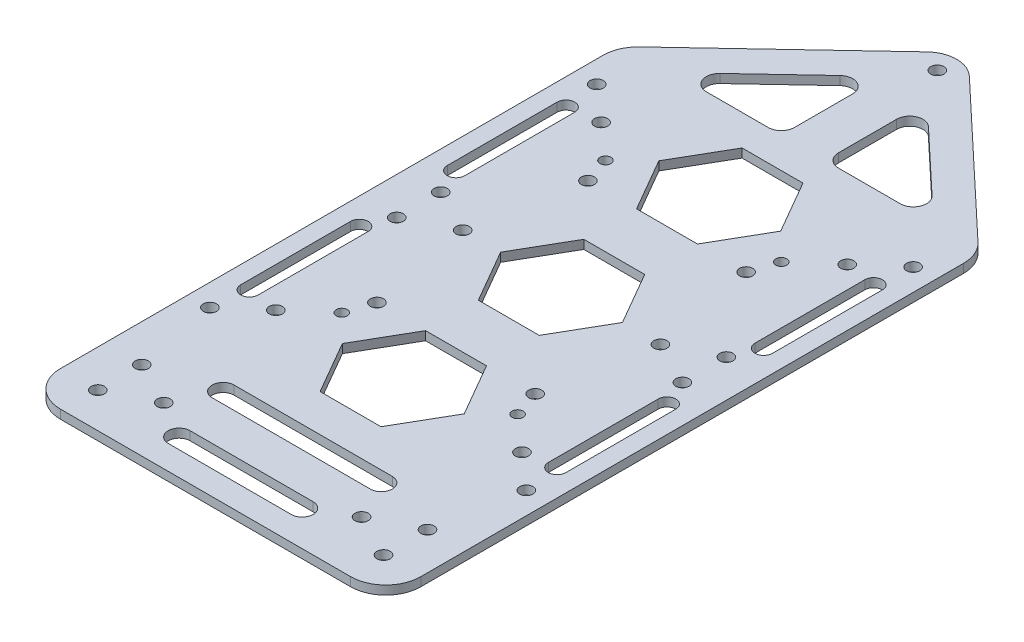
SolidWorks part; units mm, degrees
ref_plane "前视基准面" through (0, 0, 0) normal (0, 0, 1) x (1, 0, 0)
ref_plane "上视基准面" through (0, 0, 0) normal (0, 1, 0) x (1, 0, 0)
ref_plane "右视基准面" through (0, 0, 0) normal (1, 0, 0) x (0, 0, -1)
sketch "草图1" plane through (0, 0, 0) normal (0, 1, 0) x (1, 0, 0)
  line L0 (-33, -81) -> (33, -81)
  line L2 (-41, -73) -> (-41, 50.4441)
  line L4 (41, -73) -> (41, 50.4441)
  line L5 (-41, -92.5) -> (41, 92.5) construction
  line L6 (-41, 92.5) -> (41, -92.5) construction
  line L11 (-20, -30) -> (20, -30) construction
  line L12 (-20, -30) -> (-20, 30) construction
  line L13 (-20, 30) -> (20, 30) construction
  line L14 (20, -30) -> (20, 30) construction
  line L15 (-20, -30) -> (20, 30) construction
  line L16 (-20, 30) -> (20, -30) construction
  line L17 (-36, -44) -> (36, -44) construction
  line L18 (-36, -44) -> (-36, 44) construction
  line L19 (-36, 44) -> (36, 44) construction
  line L20 (36, -44) -> (36, 44) construction
  line L21 (-36, -44) -> (36, 44) construction
  line L22 (-36, 44) -> (36, -44) construction
  line L27 (-32.5, 5) -> (-32.5, -63) construction
  line L28 (-32.5, -5) -> (32.5, -5) construction
  line L29 (-32.5, -5) -> (-32.5, 5) construction
  line L30 (-32.5, 5) -> (32.5, 5) construction
  line L31 (32.5, -5) -> (32.5, 5) construction
  line L32 (-32.5, -5) -> (32.5, 5) construction
  line L33 (-32.5, 5) -> (32.5, -5) construction
  line L38 (-4.7983, 87.9825) -> (-38.4838, 56.2689)
  line L39 (4.7983, 87.9825) -> (38.4838, 56.2689)
  line L41 (-18, -24) -> (18, -24) construction
  line L42 (-18, -24) -> (-18, 24) construction
  line L43 (-18, 24) -> (18, 24) construction
  line L44 (18, -24) -> (18, 24) construction
  line L45 (-18, -24) -> (18, 24) construction
  line L46 (-18, 24) -> (18, -24) construction
  line L47 (-35, 11) -> (-35, 36) construction
  line L48 (-37, 11) -> (-37, 36)
  line L49 (-33, 11) -> (-33, 36)
  line L50 (35, 11) -> (35, 36) construction
  line L51 (33, 11) -> (33, 36)
  line L52 (37, 11) -> (37, 36)
  line L53 (35, -36) -> (35, -11) construction
  line L54 (33, -36) -> (33, -11)
  line L55 (37, -36) -> (37, -11)
  line L56 (-35, -36) -> (-35, -11) construction
  line L57 (-37, -36) -> (-37, -11)
  line L58 (-33, -36) -> (-33, -11)
  line L60 (-28, -37) -> (28, -37) construction
  line L61 (-28, -37) -> (-28, 37) construction
  line L62 (-28, 37) -> (28, 37) construction
  line L63 (28, -37) -> (28, 37) construction
  line L64 (-28, -37) -> (28, 37) construction
  line L65 (-28, 37) -> (28, -37) construction
  circle A0 centre (-20, 30) radius 1.25
  circle A1 centre (20, 30) radius 1.25
  circle A2 centre (20, -30) radius 1.25
  circle A3 centre (-20, -30) radius 1.25
  circle A4 centre (0, 85.5) radius 1.5
  circle A7 centre (-36, 44) radius 1.5
  circle A8 centre (36, 44) radius 1.5
  circle A9 centre (36, -44) radius 1.5
  circle A10 centre (-36, -44) radius 1.5
  circle A11 centre (-32.5, 5) radius 1.5
  circle A12 centre (-32.5, -5) radius 1.5
  circle A13 centre (32.5, 5) radius 1.5
  circle A14 centre (32.5, -5) radius 1.5
  circle A15 centre (22.5, 0) radius 1.5
  circle A16 centre (-22.5, 0) radius 1.5
  circle A17 centre (-32.5, -63) radius 1.5
  circle A18 centre (-32.5, -73) radius 1.5
  circle A19 centre (-22.5, -68) radius 1.5
  circle A20 centre (32.5, -63) radius 1.5
  circle A21 centre (22.5, -68) radius 1.5
  circle A22 centre (32.5, -73) radius 1.5
  arc A26 (38.4838, 56.2689) -> (41, 50.4441) centre (33, 50.4441) cw
  arc A27 (-4.7983, 87.9825) -> (4.7983, 87.9825) centre (0, 82.8859) cw
  arc A28 (-38.4838, 56.2689) -> (-41, 50.4441) centre (-33, 50.4441) ccw
  arc A29 (41, -73) -> (33, -81) centre (33, -73) cw
  arc A30 (-41, -73) -> (-33, -81) centre (-33, -73) ccw
  circle A31 centre (-18, 24) radius 1.5
  circle A32 centre (18, 24) radius 1.5
  circle A33 centre (18, -24) radius 1.5
  circle A34 centre (-18, -24) radius 1.5
  arc A35 (-37, 11) -> (-33, 11) centre (-35, 11) ccw
  arc A36 (-33, 36) -> (-37, 36) centre (-35, 36) ccw
  arc A37 (33, 11) -> (37, 11) centre (35, 11) ccw
  arc A38 (37, 36) -> (33, 36) centre (35, 36) ccw
  arc A39 (33, -36) -> (37, -36) centre (35, -36) ccw
  arc A40 (37, -11) -> (33, -11) centre (35, -11) ccw
  arc A41 (-37, -36) -> (-33, -36) centre (-35, -36) ccw
  arc A42 (-33, -11) -> (-37, -11) centre (-35, -11) ccw
  circle A43 centre (-28, 37) radius 1.5
  circle A44 centre (28, 37) radius 1.5
  circle A45 centre (-28, -37) radius 1.5
  circle A46 centre (28, -37) radius 1.5
  point P0 (0, 0)
  point P11 (0, 0)
  point P22 (0, 0)
  point P24 (0, 0)
  point P40 (0, 0)
  point P56 (-35, 23.5)
  point P78 (0, 0)
  point P83 (35, 23.5)
  point P90 (35, -23.5)
  point P97 (-35, -23.5)
  point P110 (41, 53.9)
  point P113 (0, 92.5)
  point P116 (-41, 53.9)
  dimension "D7" = 2.5
  dimension "D9" = 3
  dimension "D10" = 8
  dimension "D14" = 3
  dimension "D20" = 3
  dimension "D23" = 3
  dimension "D29" = 23.5
  dimension "D4" = 48
  dimension "D11" = 7
  dimension "D16" = 3
  dimension "D36" = 3
  dimension "D1" = 185
  dimension "D2" = 82
  dimension "D3" = 13
  dimension "D5" = 60
  dimension "D6" = 40
  dimension "D8" = 85.5
  dimension "D12" = 88
  dimension "D13" = 72
  dimension "D15" = 36
  dimension "D17" = 2
  dimension "D18" = 10
  dimension "D19" = 65
  dimension "D21" = 22.5
  dimension "D22" = 22.5
  dimension "D24" = 4
  dimension "D25" = 25
  dimension "D26" = 68
  dimension "D27" = 35
  dimension "D28" = 38.6
  dimension "D32" = 47
  dimension "D33" = 35
  dimension "D34" = 56
  dimension "D35" = 74
  dimension "D30" = 2
  dimension "D31" = 2
extrude "凸台-拉伸1" add sketch "草图1" along normal blind 2
sketch "草图3" plane through (0, 2, 0) normal (0, 1, 0) x (1, 0, 0)
  line L0 (0, 0) -> (0, 65.719) construction
  line L1 (-22.0567, 55) -> (-8, 55)
  line L2 (-5, 58) -> (-5, 71.2338)
  line L3 (-24.1131, 60.1843) -> (-10.0564, 73.4181)
  line L4 (-4.7983, 87.9825) -> (-38.4838, 56.2689) construction
  line L5 (22.0567, 55) -> (8, 55)
  line L6 (6.9282, 12) -> (-6.9282, 12)
  line L7 (-6.9282, 12) -> (-13.8564, 0)
  line L8 (-13.8564, 0) -> (-6.9282, -12)
  line L9 (-6.9282, -12) -> (6.9282, -12)
  line L10 (6.9282, -12) -> (13.8564, 0)
  line L11 (13.8564, 0) -> (6.9282, 12)
  line L12 (13.8564, 36) -> (6.9282, 48)
  line L13 (6.9282, 48) -> (-6.9282, 48)
  line L14 (-6.9282, 48) -> (-13.8564, 36)
  line L15 (-13.8564, 36) -> (-6.9282, 24)
  line L16 (-6.9282, 24) -> (6.9282, 24)
  line L17 (6.9282, 24) -> (13.8564, 36)
  line L18 (13.8564, -36) -> (6.9282, -24)
  line L19 (6.9282, -24) -> (-6.9282, -24)
  line L20 (-6.9282, -24) -> (-13.8564, -36)
  line L21 (-13.8564, -36) -> (-6.9282, -48)
  line L22 (-6.9282, -48) -> (6.9282, -48)
  line L23 (6.9282, -48) -> (13.8564, -36)
  line L24 (24.1131, 60.1843) -> (10.0564, 73.4181)
  line L25 (5, 58) -> (5, 71.2338)
  line L29 (0, 0) -> (-56.2512, 0) construction
  line L33 (-14, -73) -> (14, -73) construction
  line L34 (-14, -70.5) -> (14, -70.5)
  line L35 (-14, -75.5) -> (14, -75.5)
  line L38 (-18, -59) -> (18, -59) construction
  line L39 (-18, -56.5) -> (18, -56.5)
  line L40 (-18, -61.5) -> (18, -61.5)
  circle A0 centre (0, 0) radius 12 construction
  circle A1 centre (0, 36) radius 12 construction
  circle A2 centre (0, -36) radius 12 construction
  arc A3 (-8, 55) -> (-5, 58) centre (-8, 58) ccw
  arc A4 (-22.0567, 55) -> (-24.1131, 60.1843) centre (-22.0567, 58) cw
  arc A5 (-5, 71.2338) -> (-10.0564, 73.4181) centre (-8, 71.2338) ccw
  arc A6 (22.0567, 55) -> (24.1131, 60.1843) centre (22.0567, 58) ccw
  arc A7 (8, 55) -> (5, 58) centre (8, 58) cw
  arc A8 (5, 71.2338) -> (10.0564, 73.4181) centre (8, 71.2338) cw
  arc A15 (-14, -70.5) -> (-14, -75.5) centre (-14, -73) ccw
  arc A16 (14, -75.5) -> (14, -70.5) centre (14, -73) ccw
  arc A17 (-18, -56.5) -> (-18, -61.5) centre (-18, -59) ccw
  arc A18 (18, -61.5) -> (18, -56.5) centre (18, -59) ccw
  point P52 (0, -59)
  point P72 (0, -73)
  dimension "D3" = 24
  dimension "D7" = 3
  dimension "D1" = 10
  dimension "D2" = 7
  dimension "D4" = 12
  dimension "D5" = 12
  dimension "D6" = 7
  dimension "D8" = 36
  dimension "D9" = 5
  dimension "D10" = 9
  dimension "D13" = 28
  dimension "D14" = 5
  dimension "D15" = 73
extrude "切除-拉伸1" cut sketch "草图3" against normal through all
